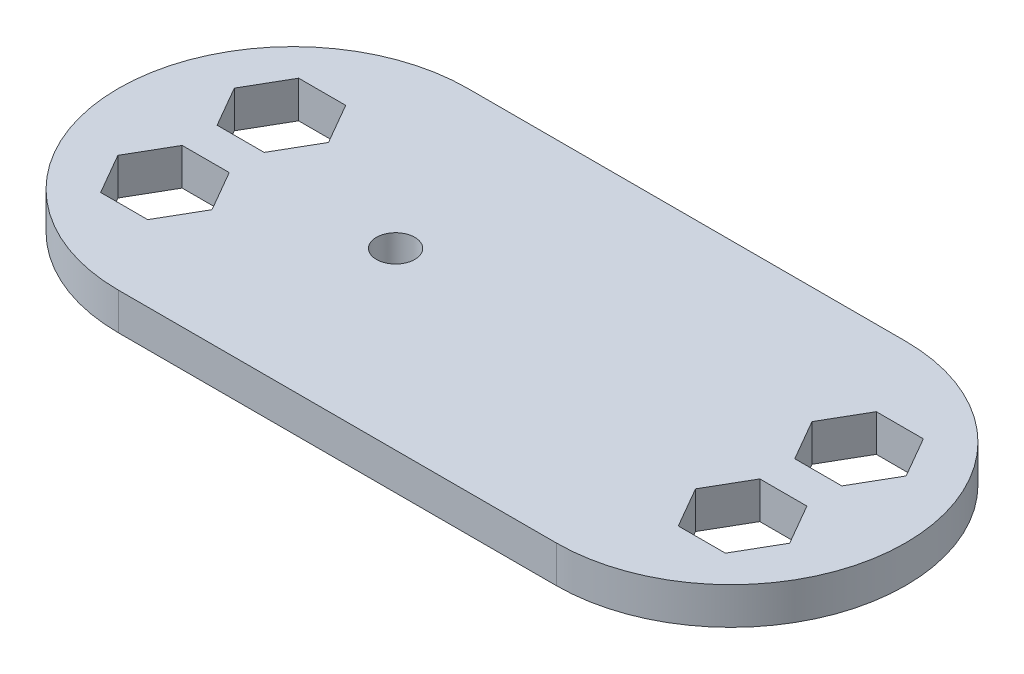
SolidWorks part; units mm, degrees
ref_plane "Front Plane" through (0, 0, 0) normal (0, 0, 1) x (1, 0, 0)
ref_plane "Top Plane" through (0, 0, 0) normal (0, 1, 0) x (1, 0, 0)
ref_plane "Right Plane" through (0, 0, 0) normal (1, 0, 0) x (0, 0, -1)
sketch "Sketch2" plane through (0, 0, 0) normal (0, 1, 0) x (1, 0, 0)
  line L0 (-145.5214, 0.9971) -> (-107.9214, 0.9971)
  line L2 (-145.5214, -29.0029) -> (-107.9214, -29.0029)
  line L4 (-151.5214, 3.0634) -> (-151.5214, -29.2944) construction
  line L9 (-101.9214, 1.8989) -> (-101.9214, -30.7894) construction
  line L10 (-126.7214, 0.9971) -> (-126.7214, -29.0029) construction
  line L11 (-149.5007, -12.5029) -> (-147.48, -9.0029)
  line L12 (-147.48, -9.0029) -> (-149.5007, -5.5029)
  line L13 (-149.5007, -5.5029) -> (-153.5421, -5.5029)
  line L14 (-153.5421, -5.5029) -> (-155.5629, -9.0029)
  line L15 (-155.5629, -9.0029) -> (-153.5421, -12.5029)
  line L16 (-153.5421, -12.5029) -> (-149.5007, -12.5029)
  line L17 (-160.5214, -14.0029) -> (-126.7214, -14.0029) construction
  line L18 (-153.5421, -15.5029) -> (-149.5007, -15.5029)
  line L19 (-155.5629, -19.0029) -> (-153.5421, -15.5029)
  line L20 (-153.5421, -22.5029) -> (-155.5629, -19.0029)
  line L21 (-149.5007, -22.5029) -> (-153.5421, -22.5029)
  line L22 (-147.48, -19.0029) -> (-149.5007, -22.5029)
  line L23 (-149.5007, -15.5029) -> (-147.48, -19.0029)
  line L24 (-103.9421, -15.5029) -> (-105.9629, -19.0029)
  line L25 (-105.9629, -19.0029) -> (-103.9421, -22.5029)
  line L26 (-103.9421, -22.5029) -> (-99.9007, -22.5029)
  line L27 (-99.9007, -22.5029) -> (-97.88, -19.0029)
  line L28 (-97.88, -19.0029) -> (-99.9007, -15.5029)
  line L29 (-99.9007, -15.5029) -> (-103.9421, -15.5029)
  line L30 (-99.9007, -12.5029) -> (-103.9421, -12.5029)
  line L31 (-97.88, -9.0029) -> (-99.9007, -12.5029)
  line L32 (-99.9007, -5.5029) -> (-97.88, -9.0029)
  line L33 (-103.9421, -5.5029) -> (-99.9007, -5.5029)
  line L34 (-105.9629, -9.0029) -> (-103.9421, -5.5029)
  line L35 (-103.9421, -12.5029) -> (-105.9629, -9.0029)
  arc A0 (-145.5214, 0.9971) -> (-145.5214, -29.0029) centre (-145.5214, -14.0029) ccw
  arc A7 (-107.9214, -29.0029) -> (-107.9214, 0.9971) centre (-107.9214, -14.0029) ccw
  circle A8 centre (-151.5214, -9.0029) radius 3.5 construction
  circle A9 centre (-151.5214, -19.0029) radius 3.5 construction
  circle A10 centre (-101.9214, -19.0029) radius 3.5 construction
  circle A11 centre (-101.9214, -9.0029) radius 3.5 construction
  dimension "D5" = 24.8
  dimension "D4" = 7
  dimension "D1" = 30
  dimension "D2" = 6
  dimension "D3" = 5
  dimension "D9" = 6
  dimension "D10" = 0
extrude "Boss-Extrude1" add sketch "Sketch2" along normal blind 3.175
sketch "Sketch3" plane through (0, 0, 0) normal (0, -1, 0) x (1, 0, 0)
  circle A0 centre (-136.7228, 13.9981) radius 1.65
extrude "Cut-Extrude1" cut sketch "Sketch3" against normal up to surface (3.175 mm away) up to face at (-126.7214, 3.175, 14.0029)
